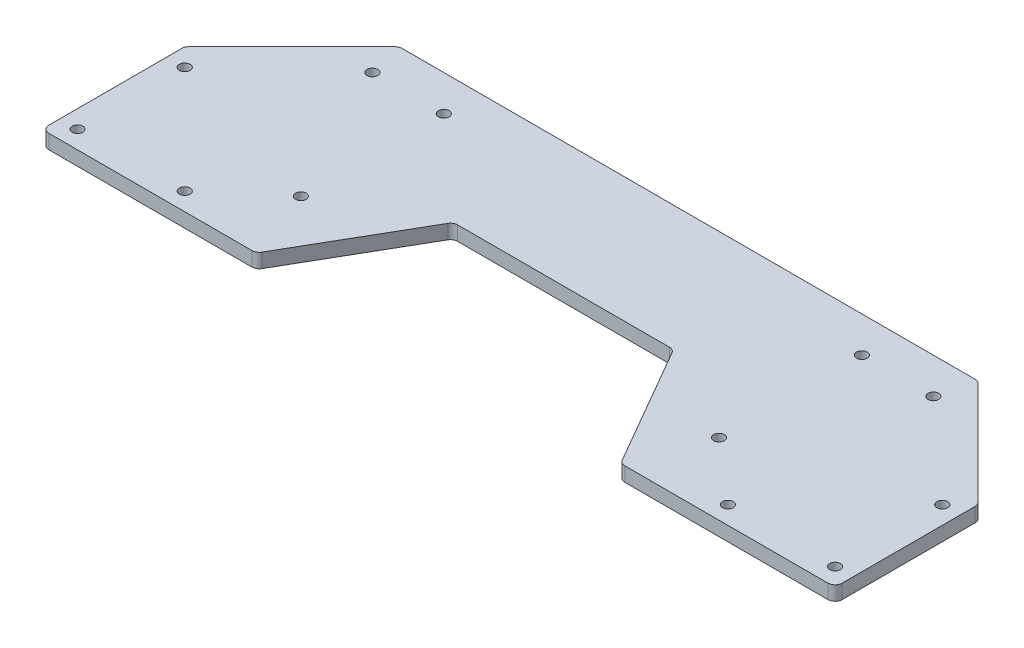
SolidWorks part; units mm, degrees
ref_plane "前视基准面" through (0, 0, 0) normal (0, 0, 1) x (1, 0, 0)
ref_plane "上视基准面" through (0, 0, 0) normal (0, 1, 0) x (1, 0, 0)
ref_plane "右视基准面" through (0, 0, 0) normal (1, 0, 0) x (0, 0, -1)
sketch "草图1" plane through (0, 0, 0) normal (0, 1, 0) x (1, 0, 0)
  line L0 (-80.2073, 5) -> (-80.2073, -35)
  line L1 (-80.2073, -35) -> (-20.2073, -35)
  line L2 (-20.2073, -35) -> (0, 0)
  line L3 (0, 0) -> (61.5855, 0)
  line L4 (61.5855, 0) -> (81.7927, -35)
  line L5 (81.7927, -35) -> (141.7927, -35)
  line L6 (141.7927, -35) -> (141.7927, 5)
  line L7 (141.7927, 5) -> (111.7927, 35)
  line L8 (111.7927, 35) -> (-50.2073, 35)
  line L9 (-50.2073, 35) -> (-80.2073, 5)
  dimension "D1" = 102
  dimension "D2" = 60
  dimension "D3" = 60
  dimension "D4" = 45
  dimension "D5" = 45
  dimension "D6" = 60
  dimension "D7" = 60
  dimension "D8" = 30
  dimension "D9" = 30
  dimension "D10" = 35
  dimension "D11" = 35
extrude "凸台-拉伸1" add sketch "草图1" along normal blind 4
sketch "草图2" plane through (0, 4, 0) normal (0, 1, 0) x (1, 0, 0)
  line L0 (-80.2073, -35) -> (-20.2073, -35) construction
  line L1 (-80.2073, 5) -> (-80.2073, -35) construction
  line L2 (111.7927, 35) -> (-50.2073, 35) construction
  line L4 (30.7927, 46.7093) -> (30.7927, -21.6751) construction
  circle A0 centre (-27.7073, -15) radius 1.5
  circle A1 centre (-27.7073, 25) radius 1.5
  circle A2 centre (-75.2073, -30) radius 1.5
  circle A3 centre (-45.2073, -30) radius 1.5
  circle A4 centre (-75.2073, 0) radius 1.5
  circle A5 centre (-47.7073, 25) radius 1.5
  circle A6 centre (109.2927, 25) radius 1.5
  circle A7 centre (136.7927, 0) radius 1.5
  circle A8 centre (106.7927, -30) radius 1.5
  circle A9 centre (136.7927, -30) radius 1.5
  circle A10 centre (89.2927, 25) radius 1.5
  circle A11 centre (89.2927, -15) radius 1.5
  dimension "D1" = 20
  dimension "D2" = 40
  dimension "D3" = 7.5
  dimension "D4" = 5
  dimension "D5" = 5
  dimension "D6" = 30
  dimension "D7" = 30
  dimension "D8" = 20
  dimension "D9" = 10
  dimension "D10" = 32.5
extrude "切除-拉伸1" cut sketch "草图2" against normal blind 10
fillet "圆角2" radius 2 10 edges at (0, 2, 0) (61.5855, 2, 0) (81.7927, 2, 35) (141.7927, 2, 35) (141.7927, 2, -5) (111.7927, 2, -35) (-50.2073, 2, -35) (-80.2073, 2, -5) (-80.2073, 2, 35) (-20.2073, 2, 35)
